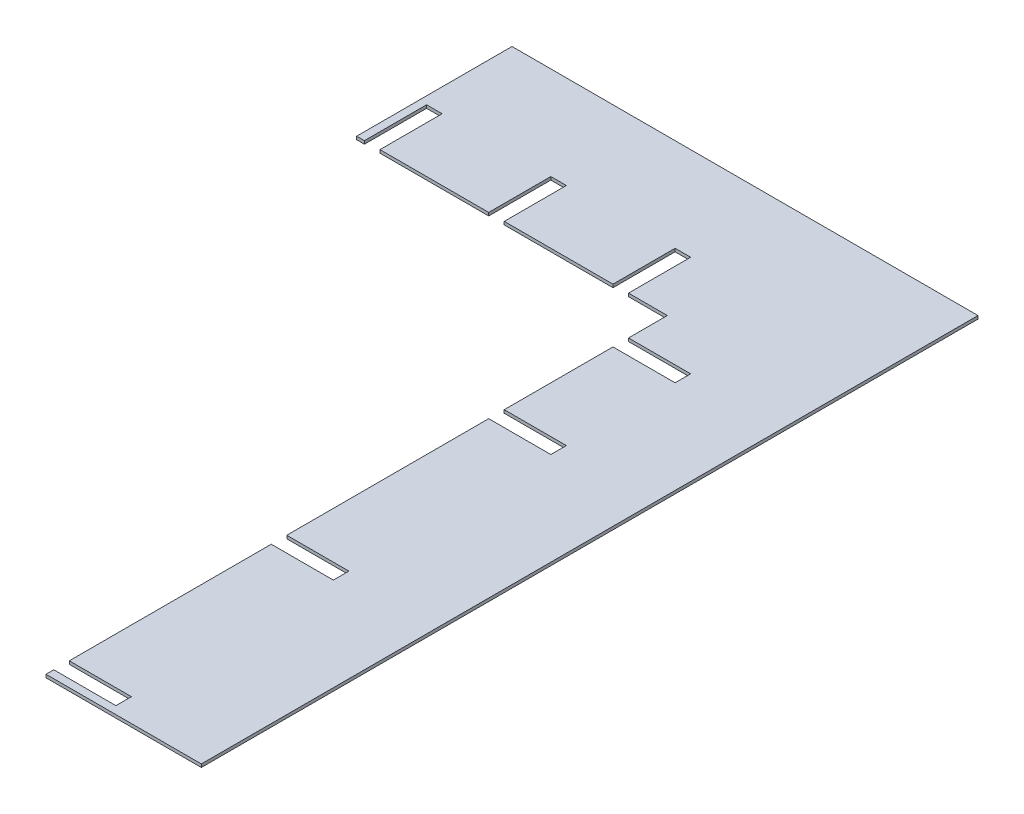
SolidWorks part; units mm, degrees
ref_plane "Front Plane" through (0, 0, 0) normal (0, 0, 1) x (1, 0, 0)
ref_plane "Top Plane" through (0, 0, 0) normal (0, 1, 0) x (1, 0, 0)
ref_plane "Right Plane" through (0, 0, 0) normal (1, 0, 0) x (0, 0, -1)
sketch "Sketch1" plane through (0, 0, 0) normal (0, 1, 0) x (1, 0, 0)
  line L6 (0, 0) -> (2.5, 0)
  line L7 (100, 0) -> (100, -12.5)
  line L8 (100, -200) -> (150, -200)
  line L9 (150, -200) -> (150, 50)
  line L14 (150, 50) -> (0, 50)
  line L15 (0, 50) -> (0, 0)
  line L16 (2.5, 0) -> (2.5, 20)
  line L17 (2.5, 20) -> (7.5, 20)
  line L18 (7.5, 20) -> (7.5, 0)
  line L23 (42.5, 0) -> (42.5, 20)
  line L24 (42.5, 20) -> (47.5, 20)
  line L29 (47.5, 20) -> (47.5, 0)
  line L30 (82.5, 0) -> (82.5, 20)
  line L35 (82.5, 20) -> (87.5, 20)
  line L36 (87.5, 20) -> (87.5, 0)
  line L41 (100, -197.5) -> (120, -197.5)
  line L42 (120, -197.5) -> (120, -192.5)
  line L43 (120, -192.5) -> (100, -192.5)
  line L46 (100, -127.5) -> (120, -127.5)
  line L47 (120, -127.5) -> (120, -122.5)
  line L48 (120, -122.5) -> (100, -122.5)
  line L51 (100, -57.5) -> (120, -57.5)
  line L52 (120, -57.5) -> (120, -52.5)
  line L53 (120, -52.5) -> (100, -52.5)
  line L54 (42.5, 0) -> (47.5, 0) construction
  line L56 (100, -17.5) -> (120, -17.5)
  line L57 (120, -17.5) -> (120, -12.5)
  line L58 (120, -12.5) -> (100, -12.5)
  line L59 (100, -197.5) -> (100, -200)
  line L60 (100, -127.5) -> (100, -192.5)
  line L61 (100, -57.5) -> (100, -122.5)
  line L62 (100, -17.5) -> (100, -52.5)
  line L63 (87.5, 0) -> (100, 0)
  line L64 (47.5, 0) -> (82.5, 0)
  line L65 (7.5, 0) -> (42.5, 0)
  line L66 (2.5, 0) -> (7.5, 0) construction
  line L69 (82.5, 0) -> (87.5, 0) construction
  line L71 (100, -12.5) -> (100, -17.5) construction
  line L72 (100, -52.5) -> (100, -57.5) construction
  line L74 (100, -197.5) -> (100, -192.5) construction
  line L76 (100, -127.5) -> (100, -122.5) construction
  line L77 (5, 20) -> (5, 0) construction
  line L79 (45, 20) -> (45, 0) construction
  line L81 (85, 20) -> (85, 0) construction
  line L83 (100, -15) -> (120, -15) construction
  line L85 (100, -55) -> (120, -55) construction
  line L87 (100, -125) -> (120, -125) construction
  line L89 (100, -195) -> (120, -195) construction
  point P48 (110, -125)
  point P50 (110, -195)
  point P51 (5, 10)
  dimension "D1" = 50
  dimension "D2" = 50
  dimension "D3" = 100
  dimension "D4" = 200
  dimension "D5" = 15
  dimension "D6" = 40
  dimension "D7" = 20
  dimension "D8" = 5
  dimension "D9" = 5
  dimension "D10" = 70
  dimension "D11" = 70
  dimension "D12" = 15
  dimension "D13" = 5
extrude "Boss-Extrude1" add sketch "Sketch1" along normal blind 1
